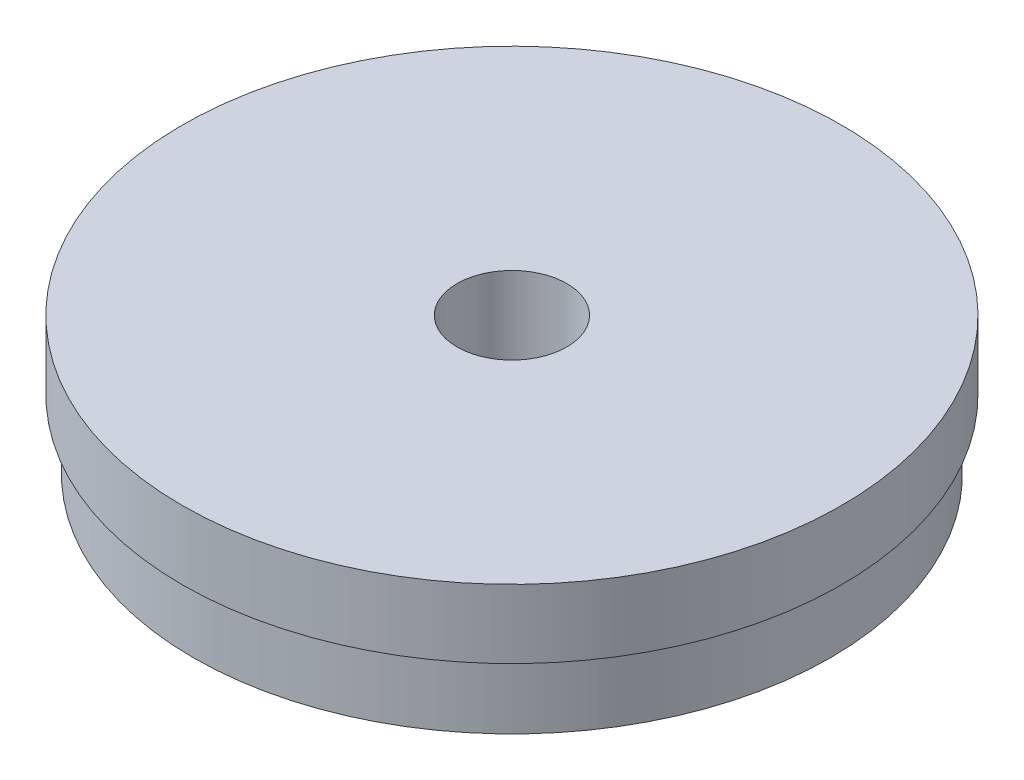
SolidWorks part; units mm, degrees
ref_plane "Front Plane" through (0, 0, 0) normal (0, 0, 1) x (1, 0, 0)
ref_plane "Top Plane" through (0, 0, 0) normal (0, 1, 0) x (1, 0, 0)
ref_plane "Right Plane" through (0, 0, 0) normal (1, 0, 0) x (0, 0, -1)
sketch "Sketch1" plane through (0, 0, 0) normal (0, 0, 1) x (1, 0, 0)
  line L0 (0, 53.1607) -> (0, -48.5179) construction
  line L1 (0, 48.0536) -> (120, 48.0536)
  line L2 (120, 48.0536) -> (120, 23.0536)
  line L3 (120, 23.0536) -> (116, 23.0536)
  line L4 (116, 23.0536) -> (116, -1.9464)
  line L5 (116, -1.9464) -> (0, -1.9464)
  line L6 (0, -1.9464) -> (0, 48.0536)
  dimension "D1" = 120
  dimension "D2" = 25
  dimension "D3" = 25
  dimension "D4" = 4
revolve "Revolve1" add sketch "Sketch1" angle 360 about L0
sketch "Sketch2" plane through (0, 48.0536, 0) normal (0, 1, 0) x (1, 0, 0)
  circle A0 centre (0, 0) radius 20
  dimension "D1" = 40
extrude "Cut-Extrude1" cut sketch "Sketch2" against normal through all
